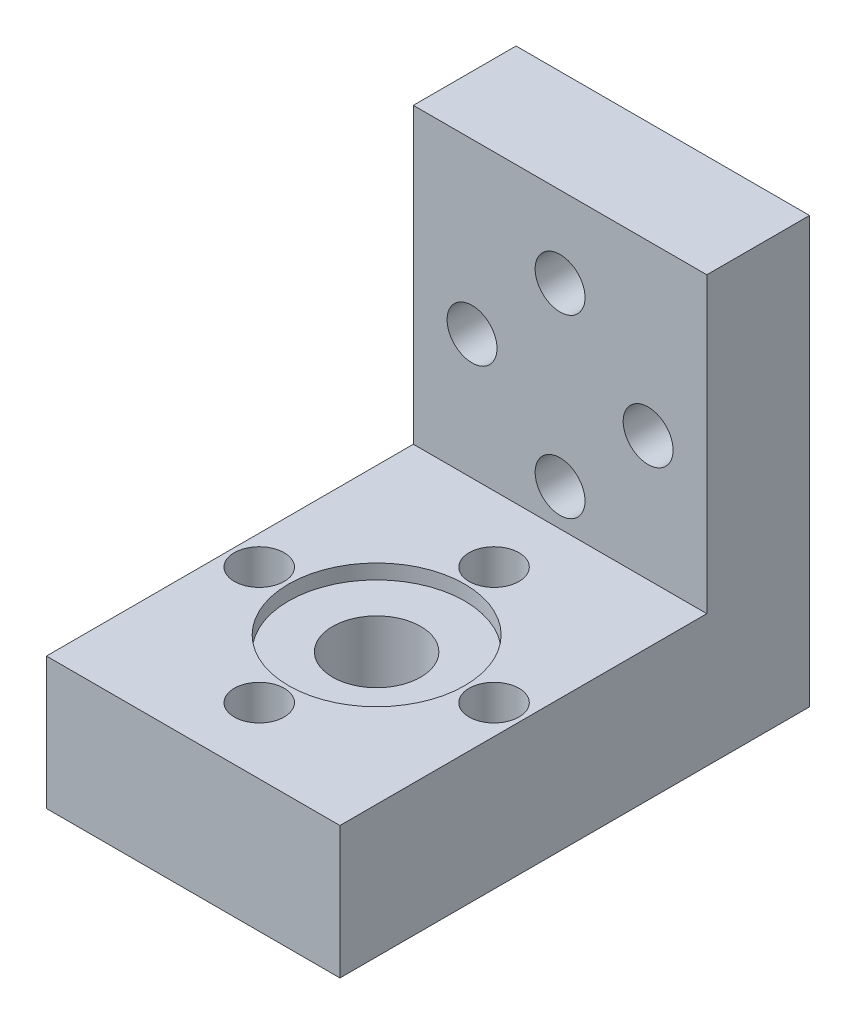
SolidWorks part; units mm, degrees
ref_plane "Front Plane" through (0, 0, 0) normal (0, 0, 1) x (1, 0, 0)
ref_plane "Top Plane" through (0, 0, 0) normal (0, 1, 0) x (1, 0, 0)
ref_plane "Right Plane" through (0, 0, 0) normal (1, 0, 0) x (0, 0, -1)
sketch "Sketch1" plane through (0, 0, 0) normal (1, 0, 0) x (0, 0, -1)
  line L0 (0, 0) -> (-50, 0)
  line L1 (-50, 0) -> (-50, 18)
  line L2 (-50, 18) -> (0, 18)
  line L3 (0, 18) -> (0, 58)
  line L4 (0, 58) -> (14, 58)
  line L5 (14, 58) -> (14, 0)
  line L6 (14, 0) -> (0, 0)
  dimension "D1" = 50
  dimension "D2" = 18
  dimension "D3" = 58
  dimension "D4" = 14
extrude "Boss-Extrude2" add sketch "Sketch1" along normal blind 40
sketch "Sketch4" plane through (0, 18, 0) normal (0, 1, 0) x (1, 0, 0)
  circle A0 centre (20, -25) radius 12
extrude "Cut-Extrude4" cut sketch "Sketch4" against normal blind 2
sketch "Sketch5" plane through (0, 16, 0) normal (0, 1, 0) x (1, 0, 0)
  circle A0 centre (20, -25) radius 6
extrude "Cut-Extrude5" cut sketch "Sketch5" against normal through all
sketch "Sketch6" plane through (0, 18, 0) normal (0, 1, 0) x (1, 0, 0)
  circle A0 centre (20, -9) radius 3.4
  circle A3 centre (36, -25) radius 3.4
  circle A4 centre (20, -41) radius 3.4
  circle A5 centre (4, -25) radius 3.4
  point P11 (20, -25)
  dimension "D1" = 4
extrude "Cut-Extrude6" cut sketch "Sketch6" against normal through all
sketch "Sketch7" plane through (0, 0, 0) normal (0, 0, 1) x (1, 0, 0)
  circle A0 centre (20, 47) radius 3.4
  circle A1 centre (32, 35) radius 3.4
  circle A2 centre (20, 23) radius 3.4
  circle A3 centre (8, 35) radius 3.4
  point P2 (20, 35)
  point P3 (20, 35)
  dimension "D1" = 4
extrude "Cut-Extrude7" cut sketch "Sketch7" against normal through all
equation "\"L1\"= 50mm"
equation "\"h1\"= 18mm"
equation "\"w1\"= 40mm"
equation "\"l2\"= 14mm"
equation "\"h2\"= 58mm"
equation "\"w2\"= 40mm"
